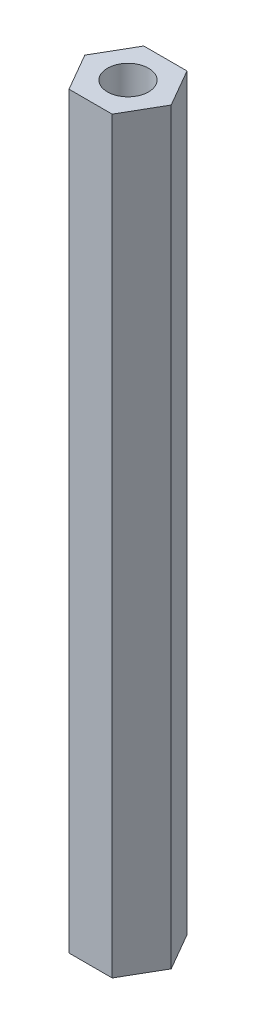
SolidWorks part; units mm, degrees
material "AISI 304"
ref_plane "前视基准面" through (0, 0, 0) normal (0, 0, 1) x (1, 0, 0)
ref_plane "上视基准面" through (0, 0, 0) normal (0, 1, 0) x (1, 0, 0)
ref_plane "右视基准面" through (0, 0, 0) normal (1, 0, 0) x (0, 0, -1)
other "Configuration Table"
sketch "草图1" plane through (0, 0, 0) normal (0, 1, 0) x (1, 0, 0)
  line L1 (3.4641, 0) -> (1.7321, 3)
  line L2 (1.7321, 3) -> (-1.7321, 3)
  line L3 (-1.7321, 3) -> (-3.4641, 0)
  line L4 (-3.4641, 0) -> (-1.7321, -3)
  line L5 (-1.7321, -3) -> (1.7321, -3)
  line L6 (1.7321, -3) -> (3.4641, 0)
  circle A0 centre (0, 0) radius 3 construction
  dimension "D1" = 6
extrude "凸台-拉伸1" add sketch "草图1" along normal mid plane 60
hole_wizard "M4 螺纹孔1" positions "草图2" profile "草图3" tap size "M4" standard "GB"
sketch "草图2" plane through (0, 30, 0) normal (0, 1, 0) x (1, 0, 0)
  point P0 (0, 0)
  point P3 (0, 0)
  point P6 (0, 0)
cosmetic thread "孔螺蚊线1" parameters "D1"=8, "D2"=4
sketch "草图3" plane through (0, 30, 0) normal (1, 0, 0) x (0, 0, 1)
  line L0 (0, 0) -> (0, 11.0914)
  line L1 (0, 11.0914) -> (1.65, 10.1)
  line L2 (1.65, 10.1) -> (1.65, 0)
  line L5 (1.65, 0) -> (0, 0)
  line L10 (0, 11.0914) -> (-1.65, 10.1) construction
  line L11 (0, -6.35) -> (0, 107.95) construction
  dimension "螺纹孔钻头直径" = 3.3
  dimension "螺纹孔钻头深度" = 10.1
  dimension "导头角度" = 118
mirror "镜向1" about plane through (0, 0, 0) normal (0, 1, 0) of "M4 螺纹孔1"
